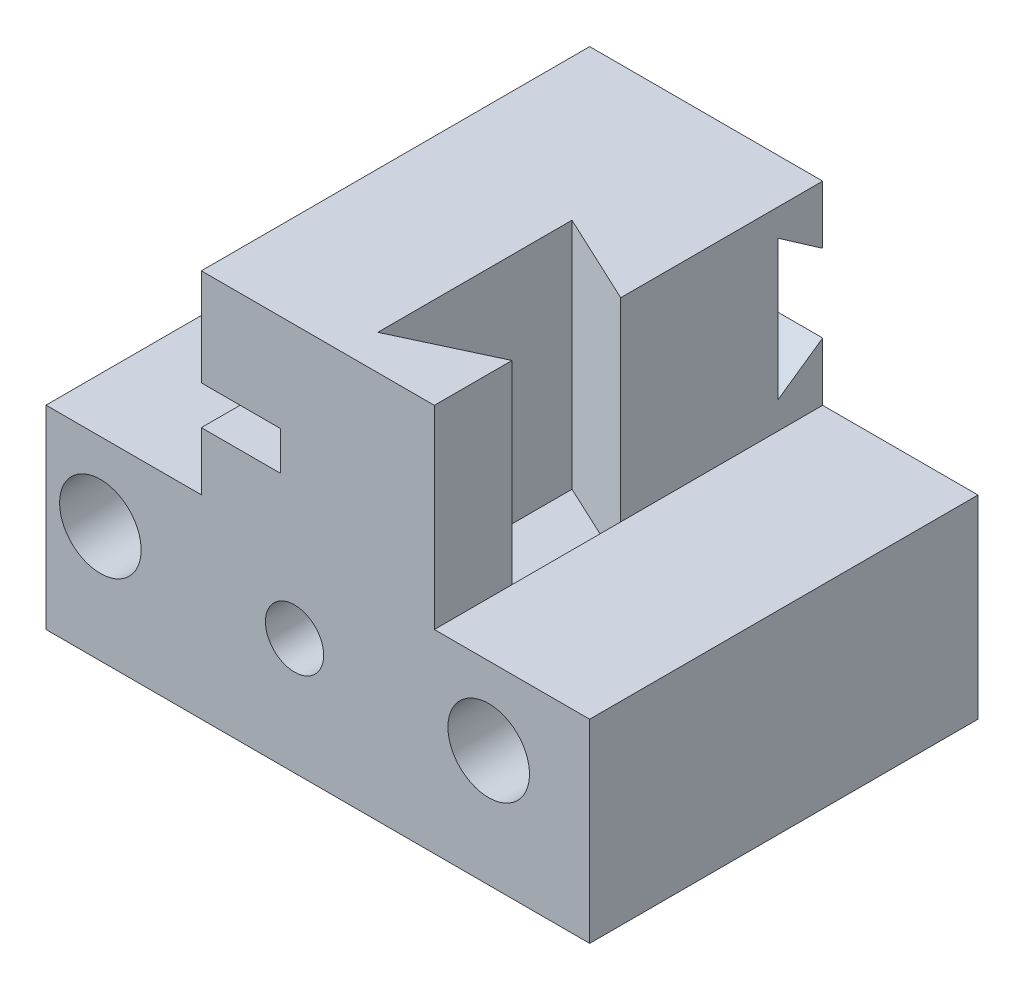
SolidWorks part; units mm, degrees
material "Polyetheretherketone (PEEK)"
ref_plane "Front Plane" through (0, 0, 0) normal (0, 0, 1) x (1, 0, 0)
ref_plane "Top Plane" through (0, 0, 0) normal (0, 1, 0) x (1, 0, 0)
ref_plane "Right Plane" through (0, 0, 0) normal (1, 0, 0) x (0, 0, -1)
ref_plane "Plane1" through (0, 4, 0) normal (0, 1, 0) x (-1, 0, 0)
sketch "Sketch1" plane through (0, 4, 0) normal (0, 1, 0) x (-1, 0, 0)
  line L0 (0, 0) -> (0, 5)
  line L1 (0, 5) -> (-7, 5)
  line L2 (-7, 5) -> (-7, 0)
  line L3 (-7, 0) -> (0, 0)
  dimension "D1" = 5
  dimension "D2" = 7
extrude "Boss-Extrude1" add sketch "Sketch1" against normal blind 5
hole_wizard "Hole1" positions "Sketch7" profile "Sketch6" legacy end condition through all
sketch "Sketch7" plane through (0, 0, 0) normal (0, 0, -1) x (-1, 0, 0)
  point P0 (-5.7, 0.5)
  point P1 (-0.7, 0.5)
  dimension "D1" = 5
  dimension "D2" = 1.5
  dimension "D3" = 0.7
  dimension "D4" = 5.7
sketch "Sketch6" plane through (5.7, 0.5, 0) normal (1, 0, 0) x (0, 1, 0)
  line L0 (0, 0) -> (0, 5)
  line L1 (0, 5) -> (0.525, 5)
  line L2 (0.525, 5) -> (0.525, 1.2)
  line L3 (0.525, 1.2) -> (0.65, 1.2)
  line L4 (0.65, 1.2) -> (0.65, 0)
  line L5 (0.65, 0) -> (0, 0)
  line L6 (0, 110) -> (0, -10) construction
  dimension "Diameter" = 1.05
  dimension "Depth" = 5
  dimension "C-Bore Diameter" = 1.3
  dimension "C-Bore Depth" = 1.2
sketch "Sketch20" plane through (7, 0, 0) normal (1, 0, 0) x (0, 0, -1)
  line L0 (0, -1) -> (0, 4) construction
  line L1 (-5, 4) -> (0, 4)
  line L2 (-5, 4) -> (-5, 1.5)
  line L3 (-5, 1.5) -> (0, 1.5)
  line L4 (0, 4) -> (0, 1.5)
  line L5 (0, -1) -> (0, 4) construction
  point P7 (0, 2.7)
  dimension "D1" = 2.5
extrude "Cut-Extrude11" cut sketch "Sketch20" against normal blind 2
sketch "Sketch22" plane through (0, 0, 0) normal (0, 0, -1) x (-1, 0, 0)
  line L0 (-7, -1) -> (0, -1) construction
  line L1 (-7, -1) -> (-7, 1.5) construction
  line L3 (-5.8, 1.15) -> (-7, 1.15)
  line L4 (-5.8, 1.15) -> (-5.8, 1.05)
  line L5 (-5.8, 1.05) -> (-7, 1.05)
  line L6 (-7, 1.15) -> (-7, 1.05)
  circle A0 centre (-5.8, 0.5) radius 0.65
  dimension "D1" = 1.3
  dimension "D2" = 1.5
  dimension "D3" = 1.2
extrude "Cut-Extrude12" [suppressed] cut sketch "Sketch22" against normal blind 1.2
hole_wizard "M1.0x0.25 Tapped Hole1" positions "Sketch32" profile "Sketch34" tap size "M1.0x0.25" standard "ANSI Metric" end condition up to next
sketch "Sketch32" plane through (0, 0, 0) normal (0, 0, -1) x (-1, 0, 0)
  line L0 (-5.7, 0.5) -> (-0.7, 0.5) construction
  circle A0 centre (-0.7, 0.5) radius 0.65 construction
  circle A1 centre (-0.7, 0.5) radius 0.65
  circle A4 centre (-5.7, 0.5) radius 0.65 construction
  circle A5 centre (-5.7, 0.5) radius 0.65
  point P20 (-3.2, 0.5)
cosmetic thread "Hole Thread4" parameters "D2"=25.4
sketch "Sketch34" plane through (3.2, 0.5, 0) normal (1, 0, 0) x (0, 1, 0)
  line L0 (0, 0) -> (0, 5)
  line L1 (0, 5) -> (0.375, 5)
  line L2 (0.375, 5) -> (0.375, 0)
  line L5 (0.375, 0) -> (0, 0)
  line L11 (0, -6.35) -> (0, 107.95) construction
  dimension "Thru Tap Drill Dia." = 0.75
  dimension "Thru Tap Drill Depth" = 5
ref_plane "Plane2" through (0, 4, 5) normal (0, 1, 0) x (1, 0, 0)
sketch "Sketch37" plane through (0, 0, 0) normal (-1, 0, 0) x (0, 0, 1)
  line L0 (5, -1) -> (5, 4) construction
  line L1 (5, 4.0021) -> (0, 4.0021)
  line L2 (5, 4.0021) -> (5, 1.5021)
  line L3 (5, 1.5021) -> (0, 1.5021)
  line L4 (0, 4.0021) -> (0, 1.5021)
  line L5 (0, -1) -> (0, 4) construction
  line L6 (5, 1.5) -> (0, 1.5) construction
  line L7 (0, 4) -> (5, 4) construction
  point P8 (0, 0)
  dimension "D1" = 2.5
extrude "Cut-Extrude13" cut sketch "Sketch37" against normal blind 2
sketch "Sketch41" plane through (0, 4, 0) normal (0, 1, 0) x (1, 0, 0)
  line L0 (5, -2.6) -> (3.8221, -2.05)
  line L1 (5, 0) -> (5, -5) construction
  line L2 (3.8221, -2.05) -> (3.8221, -4.55)
  line L3 (3.8221, -4.55) -> (5, -4)
  line L4 (5, -4) -> (5, -2.6)
  dimension "D1" = 1.4
  dimension "D2" = 1.3
  dimension "D3" = 2.5
  dimension "D4" = 1
  dimension "D5" = 2.6
extrude "Cut-Extrude15" cut sketch "Sketch41" against normal blind 3
sketch "Sketch43" plane through (2, 0, 0) normal (-1, 0, 0) x (0, 0, 1)
  line L0 (0, 2.2505) -> (0.5745, 1.8505)
  line L1 (0, 4) -> (0, 1.5021) construction
  line L2 (0.5745, 1.8505) -> (0.5745, 3.6505)
  line L3 (0.5745, 3.6505) -> (0, 3.2505)
  line L4 (0, 3.2505) -> (0, 2.2505)
  dimension "D1" = 0.7
  dimension "D2" = 1
  dimension "D3" = 1.8
extrude "Cut-Extrude16" cut sketch "Sketch43" against normal through all
sketch "Sketch44" plane through (0, 0, 0.5745) normal (0, 0, -1) x (-1, 0, 0)
  line L0 (-2, 1.8505) -> (-2, 3.6505) construction
  line L1 (-2, 2.2513) -> (-3.0204, 2.2513)
  line L2 (-2, 2.2513) -> (-2, 2.7505)
  line L3 (-2, 2.7505) -> (-3.0204, 2.7505)
  line L4 (-3.0204, 2.2513) -> (-3.0204, 2.7505)
extrude "Cut-Extrude17" cut sketch "Sketch44" against normal through all
